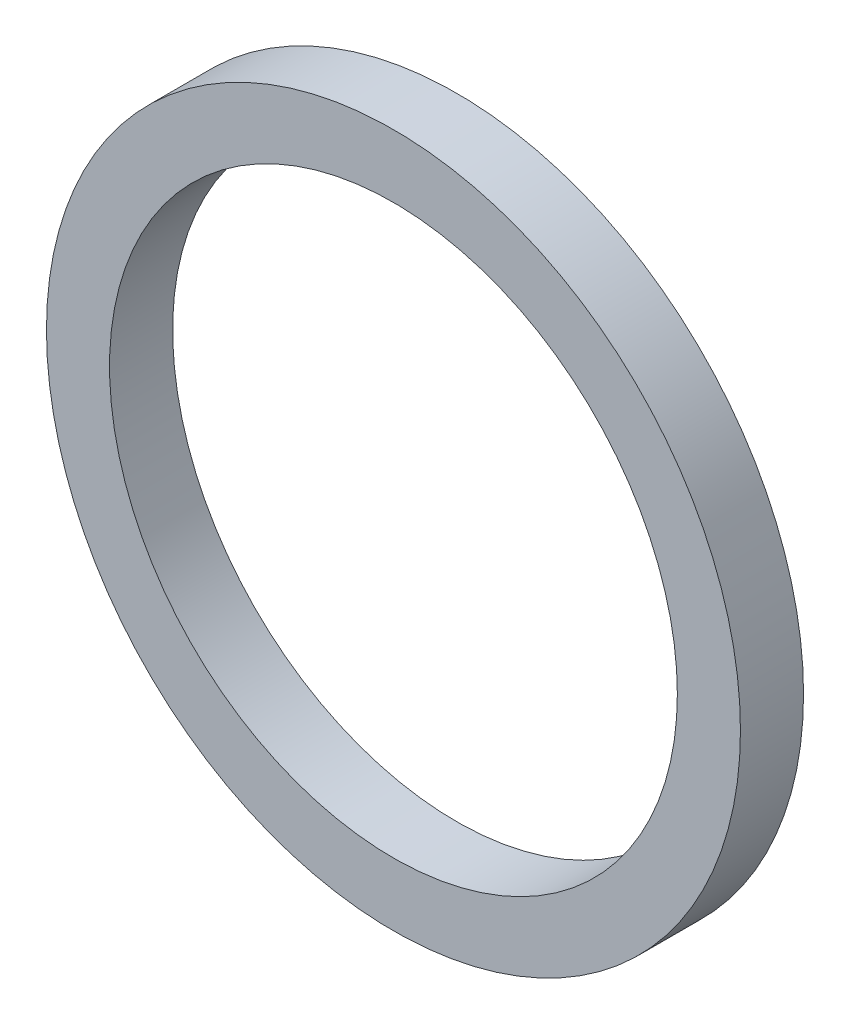
SolidWorks part; units mm, degrees
ref_plane "Front Plane" through (0, 0, 0) normal (1, 0, 0) x (0, 1, 0)
ref_plane "Top Plane" through (0, 0, 0) normal (0, 0, 1) x (0, 1, 0)
ref_plane "Right Plane" through (0, 0, 0) normal (0, 1, 0) x (-1, 0, 0)
sketch "Sketch1" plane through (0, 0, 0) normal (0, 0, 1) x (0, 1, 0)
  circle A0 centre (0, 0) radius 55
  circle A1 centre (0, 0) radius 45
  dimension "D1" = 110
  dimension "D2" = 90
extrude "Boss-Extrude1" add sketch "Sketch1" along normal blind 10
